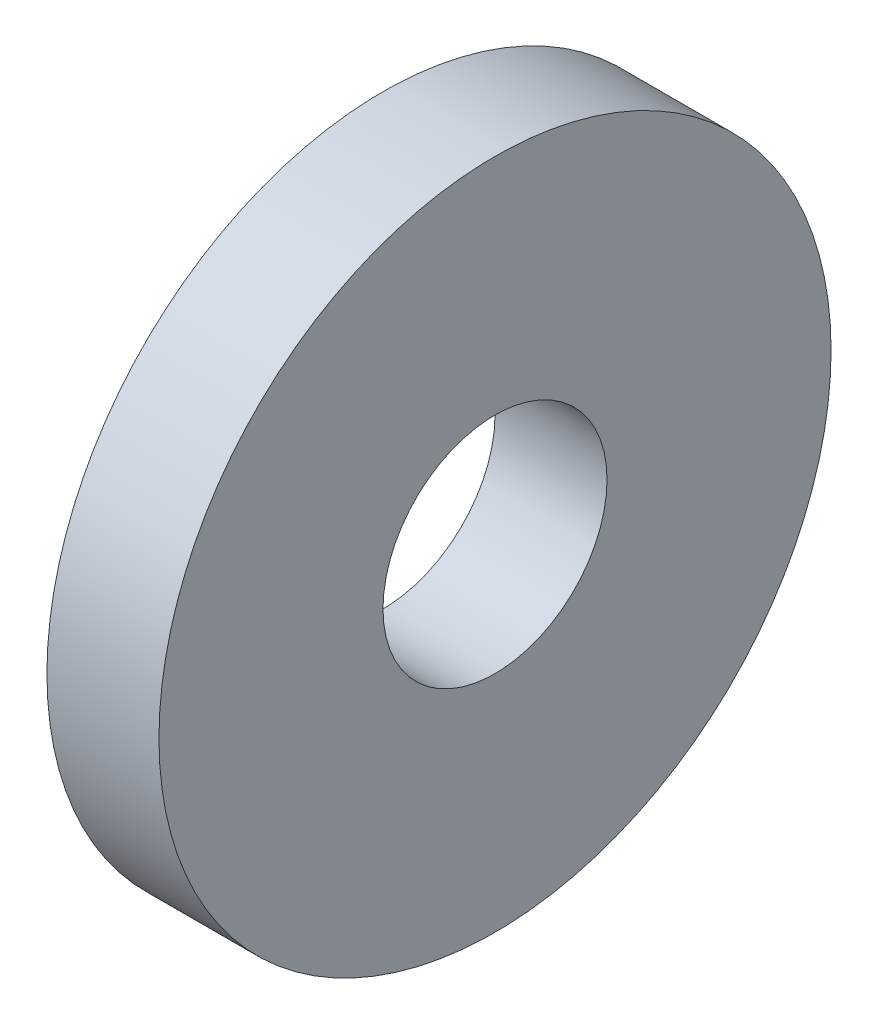
SolidWorks part; units mm, degrees
ref_plane "Front Plane" through (0, 0, 0) normal (0, 0, 1) x (1, 0, 0)
ref_plane "Top Plane" through (0, 0, 0) normal (0, 1, 0) x (1, 0, 0)
ref_plane "Right Plane" through (0, 0, 0) normal (1, 0, 0) x (0, 0, -1)
sketch "Sketch1" plane through (0, 0, 0) normal (1, 0, 0) x (0, 0, -1)
  circle A0 centre (0, 0) radius 6.35
  circle A1 centre (0, 0) radius 19.05
  dimension "D1" = 12.7
  dimension "D2" = 12.7
extrude "Boss-Extrude1" add sketch "Sketch1" along normal blind 6.35
